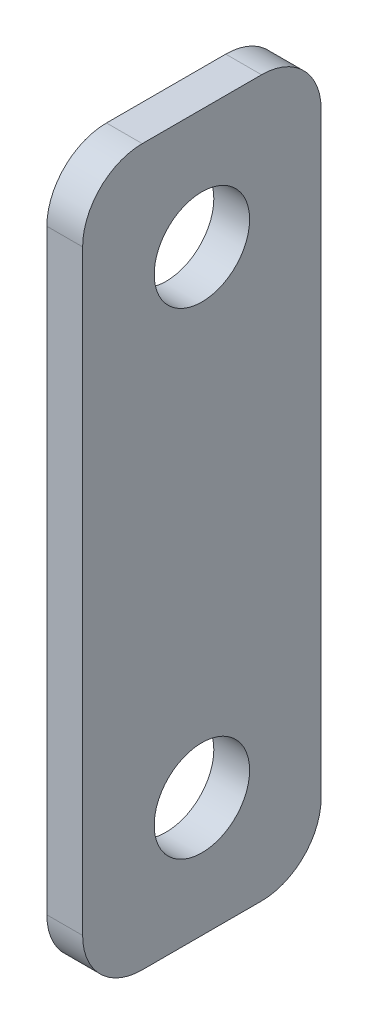
SolidWorks part; units mm, degrees
ref_plane "Front Plane" through (0, 0, 0) normal (0, 0, 1) x (1, 0, 0)
ref_plane "Top Plane" through (0, 0, 0) normal (0, 1, 0) x (1, 0, 0)
ref_plane "Right Plane" through (0, 0, 0) normal (1, 0, 0) x (0, 0, -1)
sketch "Sketch1" plane through (0, 0, 0) normal (1, 0, 0) x (0, 0, -1)
  line L1 (0, 0) -> (20, 0)
  line L2 (0, 0) -> (0, 60)
  line L3 (0, 60) -> (20, 60)
  line L4 (20, 0) -> (20, 60)
  circle A0 centre (10, 50) radius 4
  circle A1 centre (10, 10) radius 4
  dimension "D7" = 8
  dimension "D8" = 8
  dimension "D1" = 60
  dimension "D2" = 20
  dimension "D3" = 10
  dimension "D4" = 10
  dimension "D5" = 10
  dimension "D6" = 10
extrude "Boss-Extrude1" add sketch "Sketch1" along normal blind 3
fillet "Fillet1" radius 5 4 edges at (1.5, 0, -20) (1.5, 0, 0) (1.5, 60, 0) (1.5, 60, -20)
